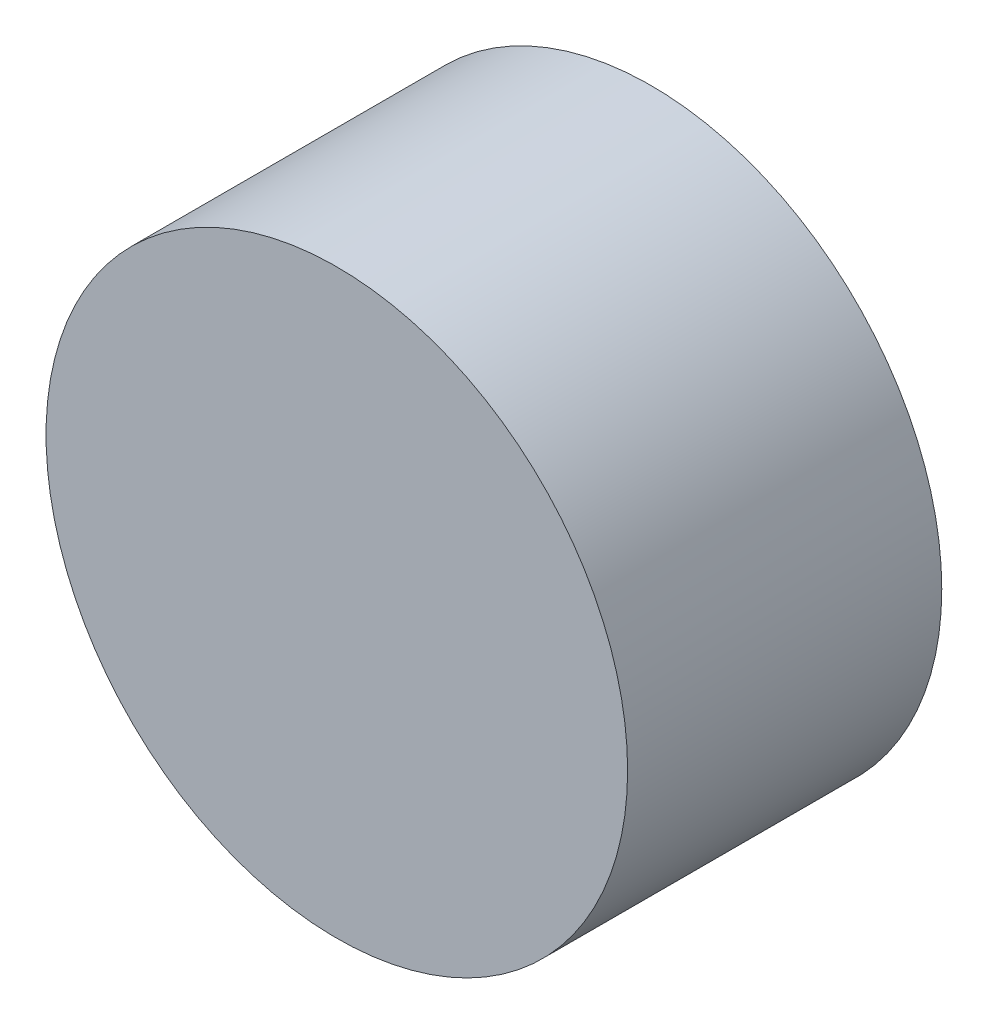
SolidWorks part; units mm, degrees
ref_plane "Front Plane" through (0, 0, 0) normal (0, 0, 1) x (1, 0, 0)
ref_plane "Top Plane" through (0, 0, 0) normal (0, 1, 0) x (1, 0, 0)
ref_plane "Right Plane" through (0, 0, 0) normal (1, 0, 0) x (0, 0, -1)
sketch "Sketch2" plane through (0, 0, 0) normal (0, 0, 1) x (1, 0, 0)
  circle A0 centre (0, 0) radius 34.25
  dimension "D1" = 68.5
extrude "Boss-Extrude1" add sketch "Sketch2" along normal blind 37
